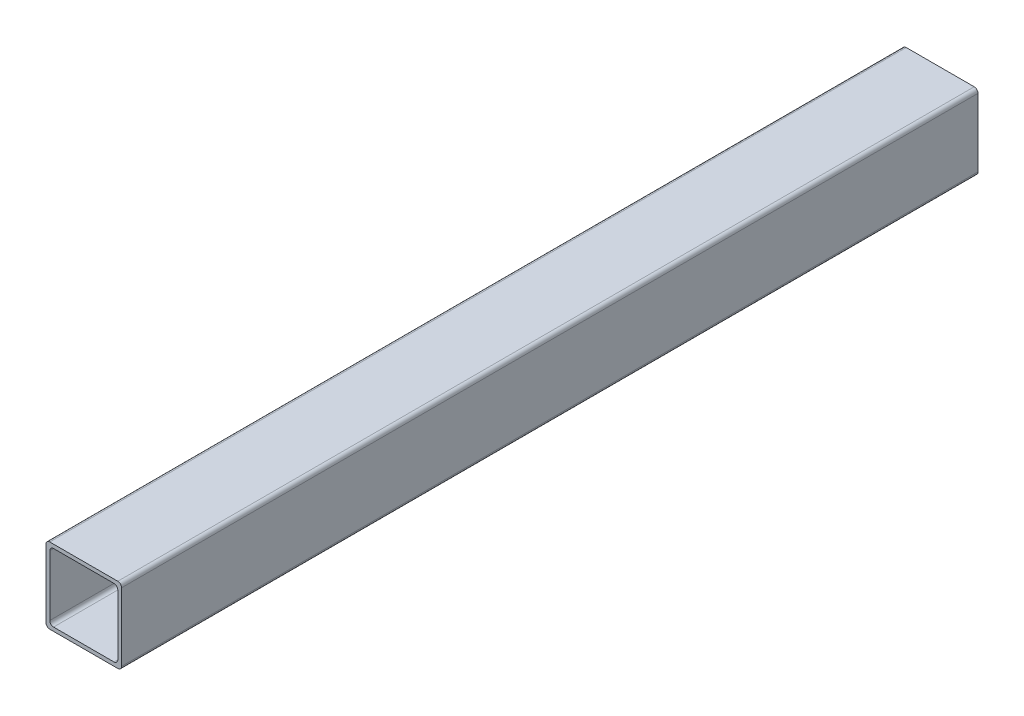
SolidWorks part; units mm, degrees
ref_plane "Płaszczyzna przednia" through (0, 0, 0) normal (0, 0, 1) x (1, 0, 0)
ref_plane "Płaszczyzna górna" through (0, 0, 0) normal (0, 1, 0) x (1, 0, 0)
ref_plane "Płaszczyzna prawa" through (0, 0, 0) normal (1, 0, 0) x (0, 0, -1)
sketch "Szkic1" plane through (0, 0, 0) normal (0, 0, 1) x (1, 0, 0)
  line L0 (3, 6) -> (3, 54)
  line L1 (3, 0) -> (57, 0)
  line L2 (0, 3) -> (0, 57)
  line L3 (3, 60) -> (57, 60)
  line L4 (60, 3) -> (60, 57)
  line L5 (0, 0) -> (42.6554, 0)
  line L6 (0, 0) -> (0, 31.4913)
  line L7 (6, 57) -> (54, 57)
  line L8 (57, 6) -> (57, 54)
  line L9 (6, 3) -> (54, 3)
  arc A0 (57, 60) -> (60, 57) centre (57, 57) cw
  arc A1 (54, 57) -> (57, 54) centre (54, 54) cw
  arc A2 (57, 0) -> (60, 3) centre (57, 3) ccw
  arc A3 (57, 6) -> (54, 3) centre (54, 6) cw
  arc A4 (3, 6) -> (6, 3) centre (6, 6) ccw
  arc A5 (3, 0) -> (0, 3) centre (3, 3) cw
  arc A6 (3, 54) -> (6, 57) centre (6, 54) cw
  arc A7 (0, 57) -> (3, 60) centre (3, 57) cw
  dimension "D1" = 3
extrude "Dodanie-wyciągnięcie1" add sketch "Szkic1" along normal blind 680 contours A7 L2 A5 L1 A2 L4 A0 L3 L0 A6 L7 A1 L8 A3 L9 A4
